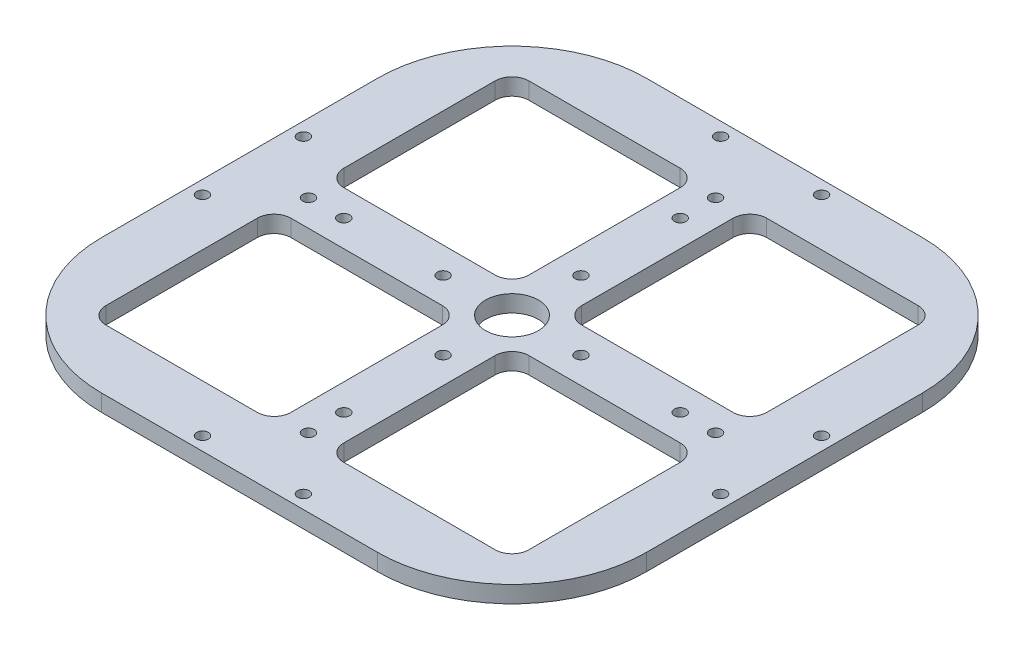
SolidWorks part; units mm, degrees
ref_plane "Front Plane" through (0, 0, 0) normal (0, 0, 1) x (1, 0, 0)
ref_plane "Top Plane" through (0, 0, 0) normal (0, 1, 0) x (1, 0, 0)
ref_plane "Right Plane" through (0, 0, 0) normal (1, 0, 0) x (0, 0, -1)
sketch "Sketch1" plane through (0, 0, 0) normal (0, 1, 0) x (1, 0, 0)
  line L0 (0, 0) -> (63.5, 0) construction
  line L1 (0, 0) -> (76.9579, 0) construction
  line L3 (-102.87, -102.87) -> (102.87, -102.87)
  line L4 (-102.87, -102.87) -> (-102.87, 102.87)
  line L5 (-102.87, 102.87) -> (102.87, 102.87)
  line L6 (102.87, -102.87) -> (102.87, 102.87)
  line L7 (-102.87, -102.87) -> (102.87, 102.87) construction
  line L8 (-102.87, 102.87) -> (102.87, -102.87) construction
  circle A1 centre (63.5, 0) radius 2.2
  circle A2 centre (0, -63.5) radius 2.2
  circle A3 centre (-63.5, 0) radius 2.2
  circle A4 centre (0, 63.5) radius 2.2
  point P14 (0, 0)
  dimension "D3" = 4.4
  dimension "D2" = 63.5
  dimension "D4" = 0
  dimension "D1" = 205.74
extrude "Boss-Extrude1" add sketch "Sketch1" along normal blind 6.35
sketch "Sketch5" plane through (0, 0, 0) normal (0, 0, 1) x (1, 0, 0)
  line L0 (0, 0) -> (0, 41.1667) construction
sketch "Sketch3" plane through (0, 6.35, 0) normal (0, 1, 0) x (1, 0, 0)
  circle A0 centre (0, 0) radius 10
  dimension "D1" = 20
extrude "Cut-Extrude2" cut sketch "Sketch3" against normal through all
sketch "Sketch4" plane through (0, 6.35, 0) normal (0, 1, 0) x (1, 0, 0)
  line L4 (-102.87, 102.87) -> (0, 0) construction
  line L5 (-79.8263, 9.9763) -> (-9.9763, 9.9763)
  line L6 (-79.8263, 9.9763) -> (-79.8263, 79.8263)
  line L7 (-79.8263, 79.8263) -> (-9.9763, 79.8263)
  line L8 (-9.9763, 9.9763) -> (-9.9763, 79.8263)
  line L9 (-79.8263, 9.9763) -> (-9.9763, 79.8263) construction
  line L10 (-79.8263, 79.8263) -> (-9.9763, 9.9763) construction
  point P0 (-44.9013, 44.9013)
  point P8 (0, 0)
  point P9 (0, 0)
  point P12 (0, 0)
  dimension "D1" = 69.85
  dimension "D2" = 63.5
extrude "Cut-Extrude3" cut sketch "Sketch4" against normal through all
fillet "Fillet1" radius 6.35 4 edges at (-9.9763, 3.175, -9.9763) (-79.8263, 3.175, -9.9763) (-79.8263, 3.175, -79.8263) (-9.9763, 3.175, -79.8263)
pattern_circular "CirPattern2" count 4 over 360 about axis through (0, 0, 0) along (0, 1, 0) of "Fillet1", "Cut-Extrude3"
fillet "Fillet2" radius 50.8 4 edges at (-102.87, 3.175, -102.87) (102.87, 3.175, -102.87) (102.87, 3.175, 102.87) (-102.87, 3.175, 102.87)
sketch "Sketch10" plane through (0, 6.35, 0) normal (0, 1, 0) x (1, 0, 0)
  circle A0 centre (19.05, -97.79) radius 2 construction
  circle A1 centre (-19.05, -97.79) radius 2 construction
  circle A2 centre (0, -76.835) radius 2 construction
  circle A3 centre (0, -26.035) radius 2 construction
  circle A4 centre (19.05, -97.79) radius 2 construction
  circle A5 centre (-19.05, -97.79) radius 2 construction
  circle A6 centre (0, -76.835) radius 2 construction
  circle A7 centre (0, -26.035) radius 2 construction
  circle A8 centre (0, -26.035) radius 2.2
  circle A9 centre (0, -76.835) radius 2.2
  circle A10 centre (-19.05, -97.79) radius 2.2
  circle A11 centre (19.05, -97.79) radius 2.2
  dimension "D1" = 4.4
extrude "Cut-Extrude6" cut sketch "Sketch10" against normal through all
sketch "Sketch11" plane through (0, 0, 0) normal (0, -1, 0) x (1, 0, 0)
  circle A0 centre (-19.05, 97.79) radius 4
  circle A1 centre (19.05, 97.79) radius 4
  circle A2 centre (0, 76.835) radius 4
  circle A3 centre (0, 26.035) radius 4
  dimension "D1" = 8
extrude "Cut-Extrude7" cut sketch "Sketch11" against normal blind 3
pattern_circular "CirPattern4" count 4 over 360 about axis through (0, 0, 0) along (0, 1, 0) of "Cut-Extrude6", "Cut-Extrude7"
equation "\"D3@Sketch1\"=4.4mm"
equation "\"D1@Sketch3\"=20mm"
equation "\"D1@Sketch10\"=4.4mm"
equation "\"D1@Sketch11\"=8mm"
equation "\"D1@Cut-Extrude7\"=3mm"
